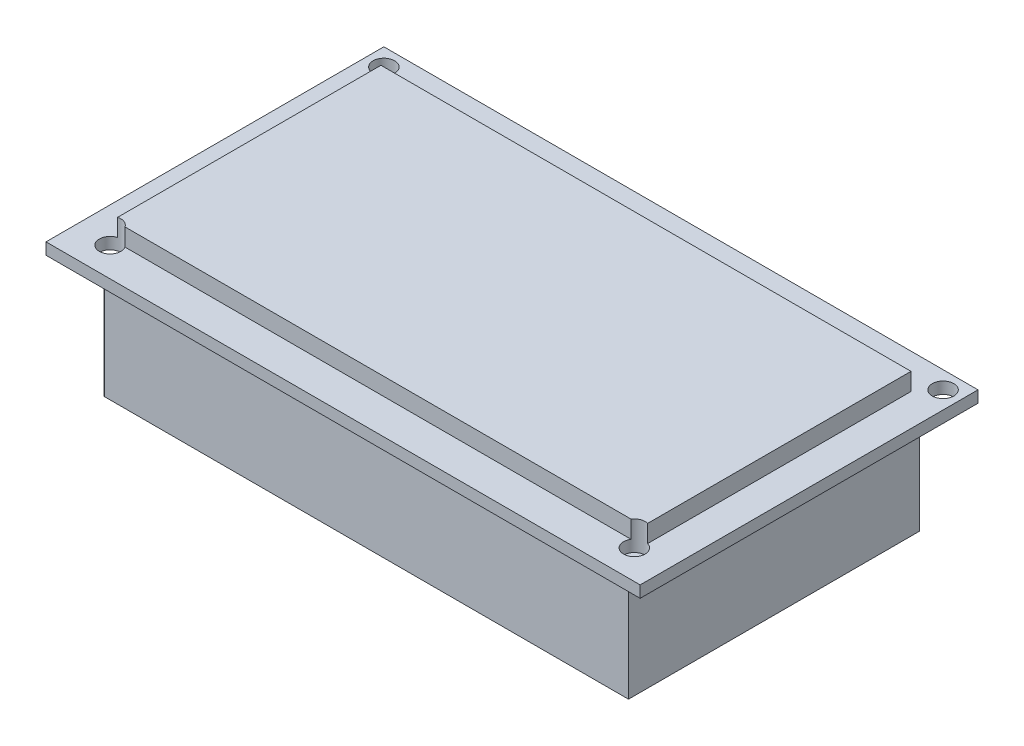
SolidWorks part; units mm, degrees
ref_plane "Alzado" through (0, 0, 0) normal (0, 0, 1) x (1, 0, 0)
ref_plane "Planta" through (0, 0, 0) normal (0, 1, 0) x (1, 0, 0)
ref_plane "Vista lateral" through (0, 0, 0) normal (1, 0, 0) x (0, 0, -1)
sketch "Croquis1" plane through (0, 0, 0) normal (0, 1, 0) x (1, 0, 0)
  line L1 (-51, 29) -> (51, 29)
  line L2 (-51, 29) -> (-51, -29)
  line L3 (-51, -29) -> (51, -29)
  line L4 (51, 29) -> (51, -29)
  line L5 (-51, 29) -> (51, -29) construction
  line L6 (-51, -29) -> (51, 29) construction
  point P0 (0, 0)
  dimension "D1" = 102
  dimension "D2" = 58
extrude "Saliente-Extruir1" add sketch "Croquis1" along normal blind 2
sketch "Croquis2" plane through (0, 2, 0) normal (0, 1, 0) x (1, 0, 0)
  line L1 (-45.5, 23) -> (45.5, 23)
  line L2 (-45.5, 23) -> (-45.5, -23)
  line L3 (-45.5, -23) -> (45.5, -23)
  line L4 (45.5, 23) -> (45.5, -23)
  line L5 (-45.5, 23) -> (45.5, -23) construction
  line L6 (-45.5, -23) -> (45.5, 23) construction
  point P0 (0, 0)
  dimension "D1" = 91
  dimension "D2" = 46
extrude "Saliente-Extruir2" add sketch "Croquis2" along normal blind 3
sketch "Croquis3" plane through (0, 0, 0) normal (0, -1, 0) x (1, 0, 0)
  line L1 (-45, 25) -> (45, 25)
  line L2 (-45, 25) -> (-45, -25)
  line L3 (-45, -25) -> (45, -25)
  line L4 (45, 25) -> (45, -25)
  line L5 (-45, 25) -> (45, -25) construction
  line L6 (-45, -25) -> (45, 25) construction
  point P0 (0, 0)
  dimension "D1" = 90
  dimension "D2" = 50
extrude "Saliente-Extruir3" add sketch "Croquis3" along normal blind 20
sketch "Croquis4" plane through (0, 0, 0) normal (0, -1, 0) x (1, 0, 0)
  line L0 (-51, 29) -> (51, 29) construction
  line L1 (-51, -29) -> (-51, 29) construction
  line L2 (51, 29) -> (51, -29) construction
  line L4 (51, -29) -> (-51, -29) construction
  circle A0 centre (-45, 24) radius 1.85
  circle A1 centre (45, 24) radius 1.85
  circle A2 centre (-48, -26) radius 1.85
  circle A3 centre (48, -26) radius 1.85
  point P18 (51, -26.2836)
  dimension "D1" = 3.7
  dimension "D3" = 6
  dimension "D4" = 3.7
  dimension "D7" = 3.7
  dimension "D10" = 3.7
  dimension "D2" = 5
  dimension "D5" = 6
  dimension "D6" = 5
  dimension "D8" = 3
  dimension "D9" = 3
  dimension "D11" = 3
  dimension "D12" = 3
extrude "Cortar-Extruir1" cut sketch "Croquis4" against normal through all
